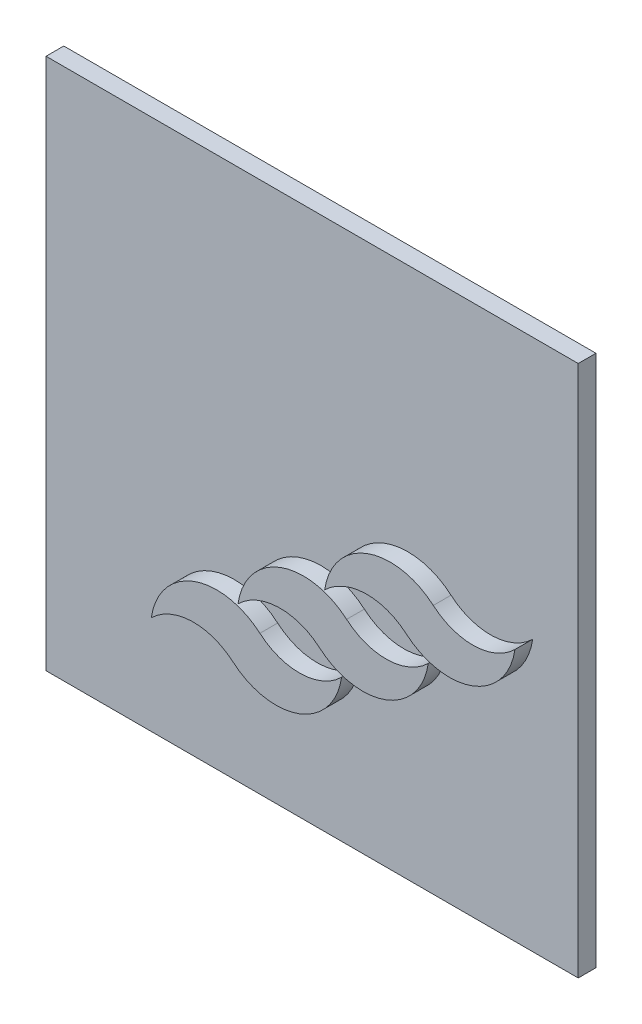
SolidWorks part; units mm, degrees
material "Obyčejná uhlíková ocel"
ref_plane "Přední rovina" through (0, 0, 0) normal (0, 0, 1) x (1, 0, 0)
ref_plane "Horní rovina" through (0, 0, 0) normal (0, 1, 0) x (1, 0, 0)
ref_plane "Pravá rovina" through (0, 0, 0) normal (1, 0, 0) x (0, 0, -1)
sketch "Skica1" plane through (0, 0, 0) normal (0, 0, 1) x (1, 0, 0)
  line L1 (0, 0) -> (300, 0)
  line L2 (0, 0) -> (0, 300)
  line L3 (0, 300) -> (300, 300)
  line L4 (300, 0) -> (300, 300)
  dimension "D1" = 300
extrude "Přidat vysunutím1" add sketch "Skica1" along normal blind 10
sketch "Skica3" plane through (0, 0, 10) normal (0, 0, 1) x (1, 0, 0)
  line L0 (115.3514, 67.0366) -> (130.5623, 88.5738) construction
  line L2 (69.3452, 65.5572) -> (176.5686, 90.0532) construction
  line L4 (69.3452, 65.5572) -> (231.3285, 169.08) construction
  arc A71 (115.3514, 67.0366) -> (176.5686, 90.0532) centre (139.6744, 95.2628) ccw
  arc A72 (115.3514, 67.0366) -> (69.3452, 65.5572) centre (93.1529, 41.2758) ccw
  arc A73 (130.5623, 88.5738) -> (176.5686, 90.0532) centre (152.7608, 114.3346) ccw
  arc A74 (130.5623, 88.5738) -> (69.3452, 65.5572) centre (106.2394, 60.3476) ccw
  arc A75 (179.4341, 119.8075) -> (118.217, 96.791) centre (155.1112, 91.5814) ccw
  arc A76 (164.2232, 98.2704) -> (118.217, 96.791) centre (142.0247, 72.5095) ccw
  arc A77 (164.2232, 98.2704) -> (225.4404, 121.287) centre (188.5462, 126.4965) ccw
  arc A78 (179.4341, 119.8075) -> (225.4404, 121.287) centre (201.6327, 145.5684) ccw
  arc A79 (228.3059, 151.0413) -> (167.0888, 128.0247) centre (203.983, 122.8151) ccw
  arc A80 (213.0951, 129.5041) -> (167.0888, 128.0247) centre (190.8965, 103.7433) ccw
  arc A81 (213.0951, 129.5041) -> (274.3122, 152.5207) centre (237.418, 157.7303) ccw
  arc A82 (228.3059, 151.0413) -> (274.3122, 152.5207) centre (250.5045, 176.8021) ccw
  point P1 (122.9569, 77.8052)
  point P10 (0, 0)
  point P27 (269.2565, 149.1467)
  point P28 (0, 0)
  point P29 (118.217, 96.791)
  point P30 (167.0888, 128.0247)
  point P31 (106.2394, 97.6078)
  point P32 (118.217, 93.7045)
  point P33 (130.5623, 90.0532)
  dimension "D1" = 3
extrude "Přidat vysunutím3" add sketch "Skica3" along normal blind 10
